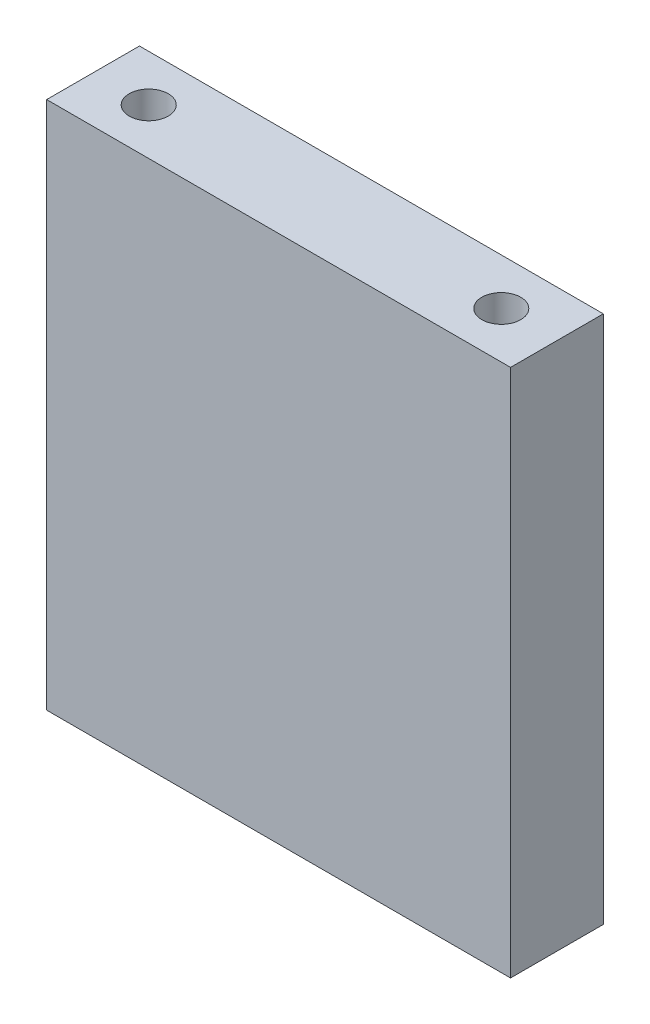
SolidWorks part; units mm, degrees
material "7075-T6, Chapa (SS)"
ref_plane "Plano frontal" through (0, 0, 0) normal (0, 0, 1) x (1, 0, 0)
ref_plane "Plano superior" through (0, 0, 0) normal (0, 1, 0) x (1, 0, 0)
ref_plane "Plano direito" through (0, 0, 0) normal (1, 0, 0) x (0, 0, -1)
sketch "Esboço1" plane through (0, 0, 0) normal (0, 0, 1) x (1, 0, 0)
  line L0 (25, 57) -> (25, 0) construction
  line L1 (0, 0) -> (50, 0)
  line L2 (0, 0) -> (0, 57)
  line L3 (0, 57) -> (50, 57)
  line L4 (50, 0) -> (50, 57)
  circle A0 centre (25, 25) radius 13
  dimension "D1" = 26
  dimension "D2" = 50
  dimension "D3" = 57
  dimension "D4" = 25
extrude "Ressalto-extrusão1" add sketch "Esboço1" along normal blind 8
sketch "Esboço3" plane through (0, 0, 8) normal (0, 0, 1) x (1, 0, 0)
  line L1 (50, 57) -> (0, 57)
  line L2 (50, 57) -> (50, 0)
  line L3 (50, 0) -> (0, 0)
  line L4 (0, 57) -> (0, 0)
extrude "Ressalto-extrusão2" add sketch "Esboço3" along normal blind 2
hole_wizard "Broca de rosquear para tarraxa de M51" positions "Esboço4" profile "Esboço5" hole size "M5" standard "ISO"
sketch "Esboço4" plane through (0, 0, 0) normal (0, -1, 0) x (-1, 0, 0)
  line L0 (0, -10) -> (-50, -10) construction
  line L1 (-50, -10) -> (-50, 0) construction
  line L2 (0, -10) -> (0, 0) construction
  point P0 (-6, -5)
  point P2 (-44, -5)
  dimension "D1" = 5
  dimension "D2" = 5
  dimension "D3" = 6
  dimension "D4" = 6
sketch "Esboço5" plane through (6, 0, 5) normal (1, 0, 0) x (0, 0, -1)
  line L0 (0, 0) -> (0, 16.2618)
  line L1 (0, 16.2618) -> (2.1, 15)
  line L2 (2.1, 15) -> (2.1, 0)
  line L5 (2.1, 0) -> (0, 0)
  line L10 (0, 16.2618) -> (-2.1, 15) construction
  line L11 (0, -6.35) -> (0, 107.95) construction
  dimension "Hole Dia." = 4.2
  dimension "Hole Depth" = 15
  dimension "Drill Angle" = 118
hole_wizard "Broca de rosquear para tarraxa de M52" positions "Esboço6" profile "Esboço7" hole size "M5" standard "ISO"
sketch "Esboço6" plane through (0, 57, 0) normal (0, 1, 0) x (1, 0, 0)
  point P0 (6, -5)
  point P3 (44, -5)
sketch "Esboço7" plane through (6, 57, 5) normal (1, 0, 0) x (0, 0, 1)
  line L0 (0, 0) -> (0, 16.2618)
  line L1 (0, 16.2618) -> (2.1, 15)
  line L2 (2.1, 15) -> (2.1, 0)
  line L5 (2.1, 0) -> (0, 0)
  line L10 (0, 16.2618) -> (-2.1, 15) construction
  line L11 (0, -6.35) -> (0, 107.95) construction
  dimension "Hole Dia." = 4.2
  dimension "Hole Depth" = 15
  dimension "Drill Angle" = 118
